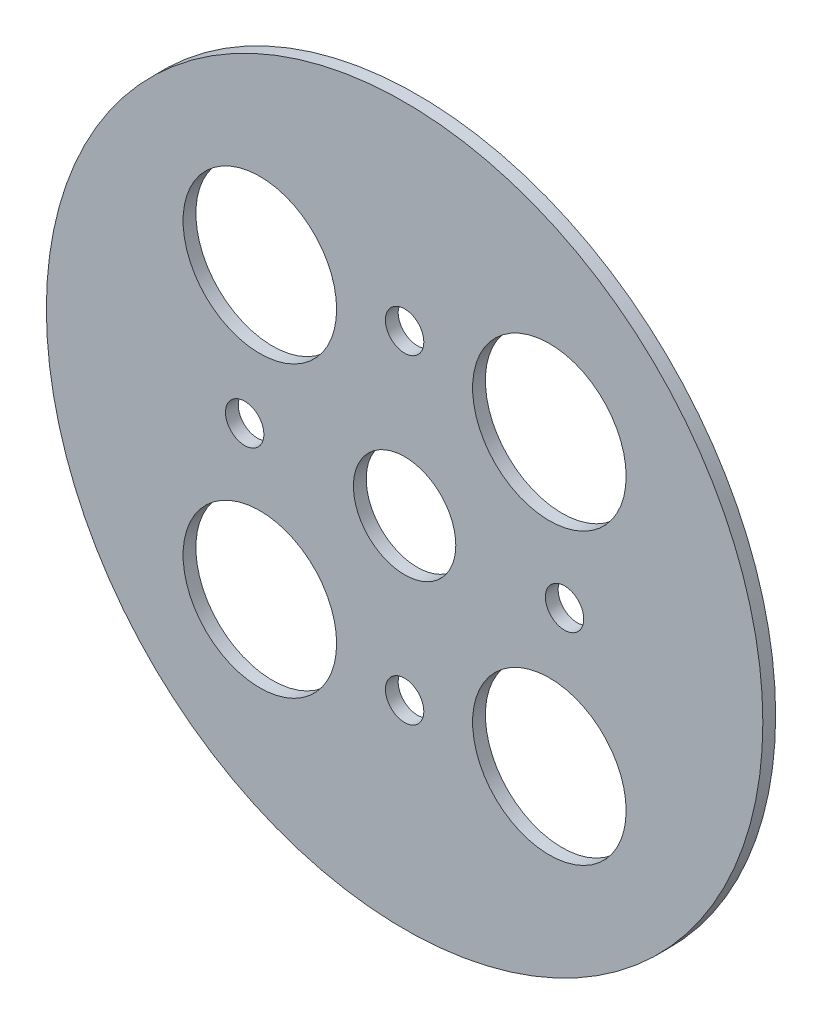
SolidWorks part; units mm, degrees
material "Thornel Mat VMA"
ref_plane "前视基准面" through (0, 0, 0) normal (0, 0, 1) x (1, 0, 0)
ref_plane "上视基准面" through (0, 0, 0) normal (0, 1, 0) x (1, 0, 0)
ref_plane "右视基准面" through (0, 0, 0) normal (1, 0, 0) x (0, 0, -1)
sketch "草图1" plane through (0, 0, 0) normal (0, 0, 1) x (1, 0, 0)
  circle A0 centre (0, 0) radius 28
  dimension "D1" = 56
extrude "凸台-拉伸1" add sketch "草图1" along normal blind 1
sketch "草图2" plane through (0, 0, 1) normal (0, 0, 1) x (1, 0, 0)
  circle A0 centre (0, 0) radius 4
  dimension "D1" = 8
extrude "切除-拉伸1" cut sketch "草图2" against normal blind 1
sketch "草图3" plane through (0, 0, 1) normal (0, 0, 1) x (1, 0, 0)
  circle A0 centre (0, 0) radius 12.5 construction
  circle A1 centre (0, 12.5) radius 1.5
  circle A2 centre (0, -12.5) radius 1.5
  circle A3 centre (12.5, 0) radius 1.5
  circle A4 centre (-12.5, 0) radius 1.5
  dimension "D1" = 25
  dimension "D2" = 3
extrude "切除-拉伸2" cut sketch "草图3" against normal up to next
sketch "草图4" plane through (0, 0, 1) normal (0, 0, 1) x (1, 0, 0)
  line L0 (0, 0) -> (0, -16) construction
  line L1 (0, 0) -> (11.3137, -11.3137) construction
  circle A0 centre (11.3137, -11.3137) radius 6
  circle A1 centre (0, 0) radius 16 construction
  circle A2 centre (-11.3137, -11.3137) radius 6
  circle A3 centre (-11.3137, 11.3137) radius 6
  circle A4 centre (11.3137, 11.3137) radius 6
  point P5 (-16.6673, 14.4801)
  point P7 (0, 0)
  point P15 (0, 0)
  dimension "D2" = 12
  dimension "D3" = 32
  dimension "D1" = 45
  dimension "D4" = 4
extrude "切除-拉伸3" cut sketch "草图4" against normal up to next
